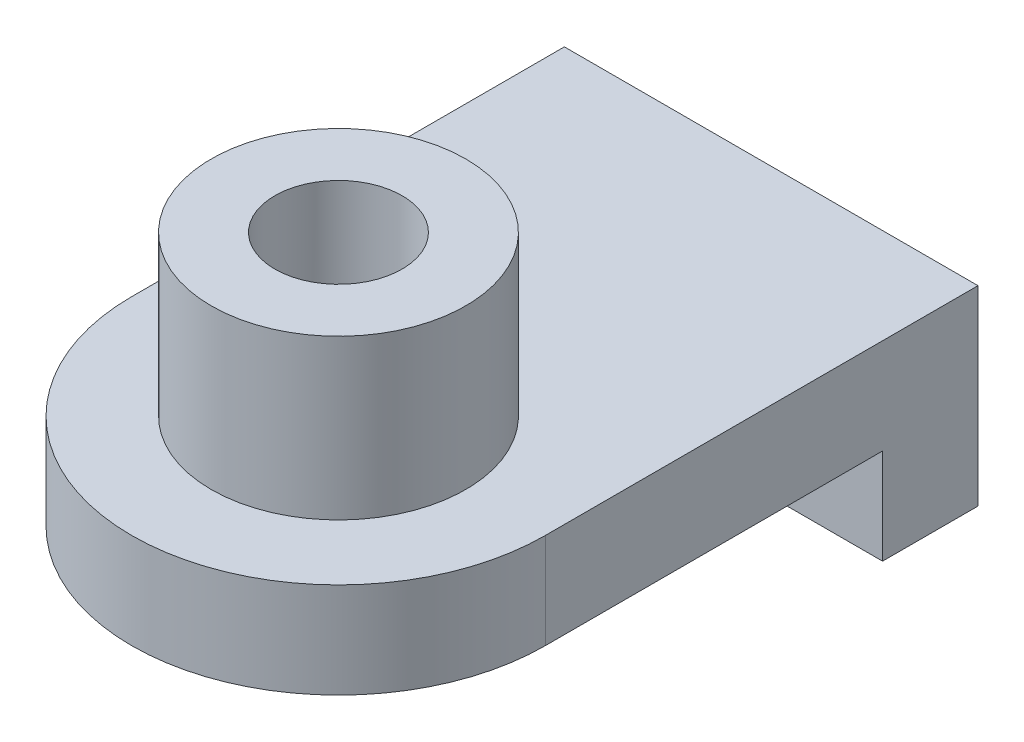
SolidWorks part; units mm, degrees
ref_plane "Front" through (0, 0, 0) normal (0, 0, 1) x (1, 0, 0)
ref_plane "Top" through (0, 0, 0) normal (0, 1, 0) x (1, 0, 0)
ref_plane "Right" through (0, 0, 0) normal (1, 0, 0) x (0, 0, -1)
sketch "Sketch1" plane through (0, 0, 0) normal (0, 1, 0) x (1, 0, 0)
  line L0 (32.5, 0) -> (32.5, 68)
  line L2 (-32.5, 68) -> (-32.5, 0)
  line L3 (-32.5, 68) -> (32.5, 68)
  arc A0 (32.5, 0) -> (-32.5, 0) centre (0, 0) cw
  dimension "D1" = 65
  dimension "D2" = 68
extrude "Base-Extrude" add sketch "Sketch1" along normal blind 15
sketch "Sketch2" plane through (32.5, 0, 0) normal (1, 0, 0) x (0, 0, -1)
  line L0 (68, 0) -> (53, 0)
  line L1 (68, 0) -> (68, -15)
  line L2 (53, -15) -> (68, -15)
  line L3 (53, -15) -> (53, 0)
  line L4 (0, 0) -> (68, 0) construction
  dimension "D1" = 15
  dimension "D2" = 15
extrude "Boss-Extrude1" add sketch "Sketch2" against normal through all
sketch "Sketch3" plane through (0, 15, 0) normal (0, 1, 0) x (-1, 0, 0)
  circle A0 centre (0, 0) radius 20
  dimension "D1" = 40
extrude "Boss-Extrude2" add sketch "Sketch3" along normal blind 25
hole_wizard "Hole1" positions "Sketch5" profile "Sketch4" legacy
sketch "Sketch5" plane through (0, 40, 0) normal (0, 1, 0) x (-1, 0, 0)
  circle A0 centre (0, 0) radius 20 construction
  point P0 (0, 0)
sketch "Sketch4" plane through (0, 40, 0) normal (1, 0, 0) x (0, 0, 1)
  line L0 (0, 0) -> (0, 25)
  line L1 (0, 25) -> (10, 25)
  line L2 (10, 25) -> (10, 0)
  line L3 (10, 0) -> (0, 0)
  line L4 (0, 110) -> (0, -10) construction
  dimension "Diameter" = 20
  dimension "Depth" = 25
